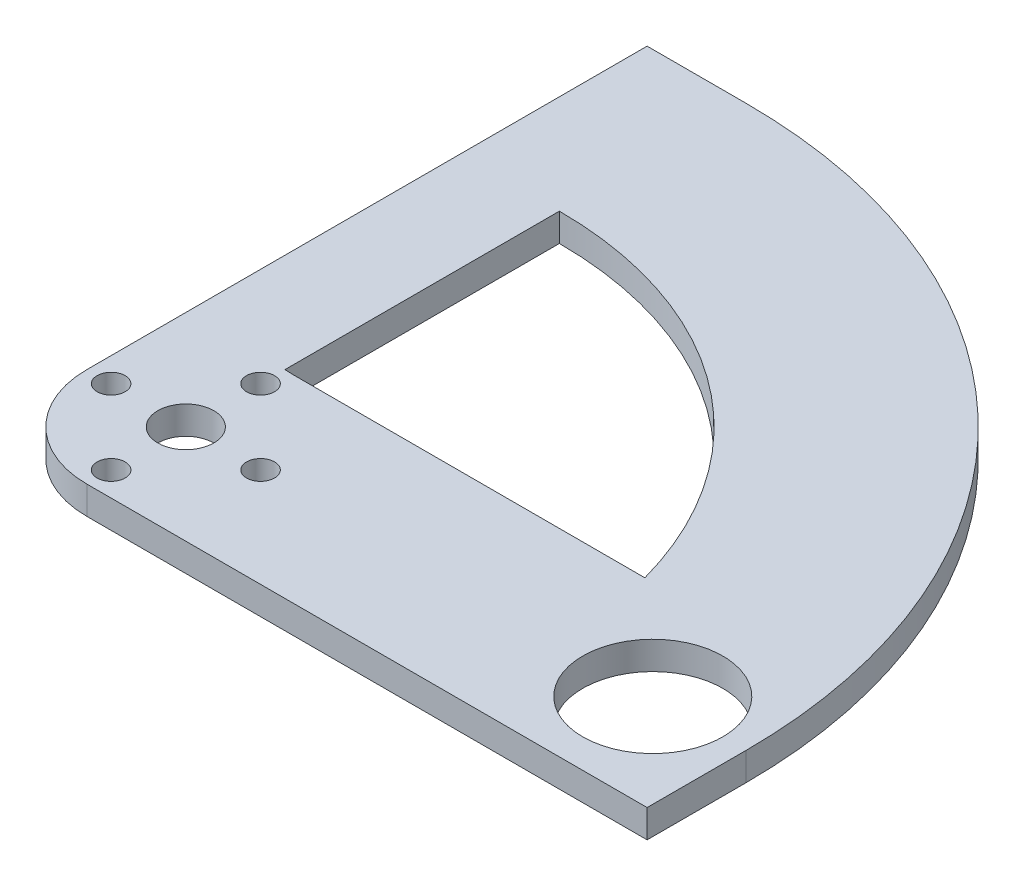
SolidWorks part; units mm, degrees
ref_plane "Front Plane" through (0, 0, 0) normal (0, 0, 1) x (1, 0, 0)
ref_plane "Top Plane" through (0, 0, 0) normal (0, 1, 0) x (1, 0, 0)
ref_plane "Right Plane" through (0, 0, 0) normal (1, 0, 0) x (0, 0, -1)
sketch "Sketch1" plane through (0, 0, 0) normal (0, 1, 0) x (1, 0, 0)
  line L0 (-10.6066, 60) -> (-10.6066, -10.6066)
  line L1 (-10.6066, -10.6066) -> (60, -10.6066)
  line L2 (0, 0) -> (-10.6066, -10.6066) construction
  line L3 (0, 0) -> (75.1686, 0) construction
  line L4 (0, 0) -> (0, 60) construction
  line L5 (60, 0) -> (60, -10.6066)
  line L6 (0, 60) -> (-10.6066, 60)
  circle A0 centre (0, 0) radius 3
  circle A1 centre (50, 0) radius 7.5
  arc A3 (0, 60) -> (60, 0) centre (0, 0) cw
  point P5 (0, 0)
  dimension "D1" = 60
  dimension "D4" = 15
  dimension "D3" = 15
  dimension "D2" = 45
  dimension "D5" = 50
extrude "Boss-Extrude1" add sketch "Sketch1" along normal blind 3
sketch "Croquis1" plane through (0, 3, 0) normal (0, 1, 0) x (1, 0, 0)
  line L0 (-10.6066, -10.6066) -> (60, -10.6066) construction
  line L1 (-10.6066, 60) -> (-10.6066, -10.6066) construction
  line L2 (0.7769, 10.5781) -> (38.5759, 10.5781)
  line L3 (0, -10.6066) -> (-10.6066, -10.6066)
  line L4 (-10.6066, -10.6066) -> (-10.6066, 40)
  line L5 (0, 0) -> (0, 52.2963) construction
  line L6 (0, 40) -> (-10.6066, 40)
  line L7 (-10.6066, 60) -> (-10.6066, -10.6066) construction
  arc A0 (0, -10.6066) -> (0.7769, 10.5781) centre (0, 0) cw
  arc A2 (38.5759, 10.5781) -> (0, 40) centre (0, 0) ccw
  point P12 (0, 0)
extrude "Cortar-Extruir1" cut sketch "Croquis1" against normal through all
sketch "Croquis2" plane through (0, 3, 0) normal (0, 1, 0) x (1, 0, 0)
  line L0 (0, 0) -> (13.4555, 0) construction
  circle A0 centre (8, 0) radius 1.5
  circle A1 centre (0, -8) radius 1.5
  circle A2 centre (-8, 0) radius 1.5
  circle A3 centre (0, 8) radius 1.5
  point P14 (0, 0)
  dimension "D1" = 3
  dimension "D3" = 8
  dimension "D2" = 4
extrude "Cortar-Extruir2" cut sketch "Croquis2" against normal through all
